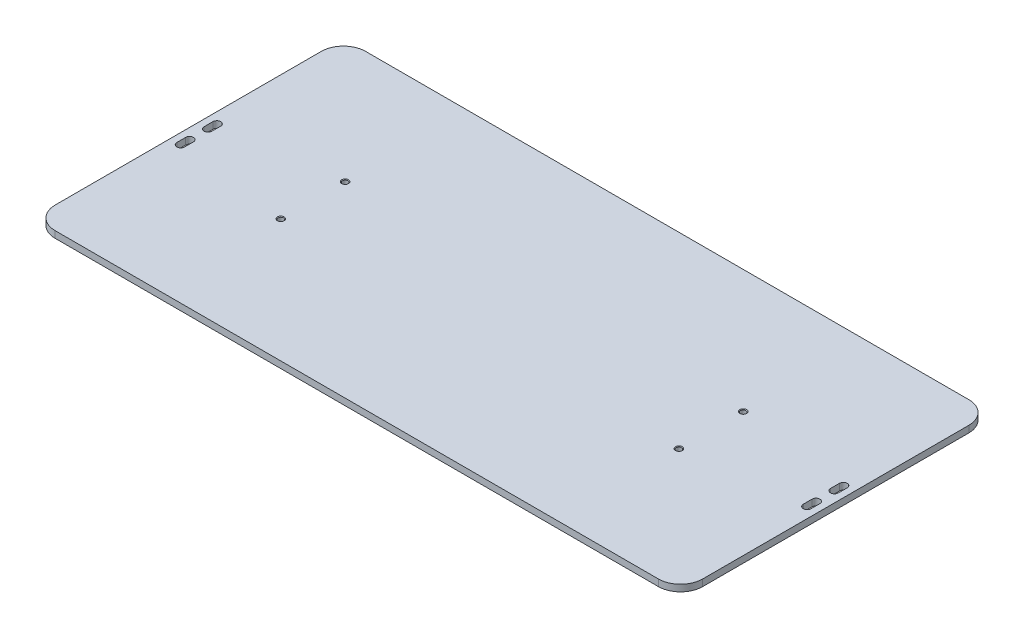
SolidWorks part; units mm, degrees
material "延性铁"
ref_plane "前视基准面" through (0, 0, 0) normal (0, 0, 1) x (1, 0, 0)
ref_plane "上视基准面" through (0, 0, 0) normal (0, 1, 0) x (1, 0, 0)
ref_plane "右视基准面" through (0, 0, 0) normal (1, 0, 0) x (0, 0, -1)
sketch "草图1" plane through (0, 0, 0) normal (0, 1, 0) x (1, 0, 0)
  line L0 (-146, 0) -> (146, 0) construction
  line L1 (-146, -70) -> (146, -70)
  line L2 (-146, -70) -> (-146, 70)
  line L3 (-146, 70) -> (146, 70)
  line L4 (146, -70) -> (146, 70)
  line L5 (-146, -70) -> (146, 70) construction
  line L6 (-146, 70) -> (146, -70) construction
  line L7 (0, 70) -> (0, -70) construction
  line L8 (-141.24, 8.14) -> (-141.24, 4.16) construction
  line L9 (-139.48, 8.14) -> (-139.48, 4.16)
  line L10 (-143, 8.14) -> (-143, 4.16)
  line L11 (-141.24, -8.14) -> (-141.24, -4.16) construction
  line L12 (-139.48, -8.14) -> (-139.48, -4.16)
  line L13 (-143, -8.14) -> (-143, -4.16)
  line L14 (141.24, 8.14) -> (141.24, 4.16) construction
  line L15 (139.48, 8.14) -> (139.48, 4.16)
  line L16 (143, 8.14) -> (143, 4.16)
  line L17 (141.24, -8.14) -> (141.24, -4.16) construction
  line L18 (139.48, -8.14) -> (139.48, -4.16)
  line L19 (143, -8.14) -> (143, -4.16)
  arc A1 (-139.48, 8.14) -> (-143, 8.14) centre (-141.24, 8.14) ccw
  arc A2 (-143, 4.16) -> (-139.48, 4.16) centre (-141.24, 4.16) ccw
  arc A3 (-139.48, -8.14) -> (-143, -8.14) centre (-141.24, -8.14) cw
  arc A4 (-143, -4.16) -> (-139.48, -4.16) centre (-141.24, -4.16) cw
  arc A5 (139.48, 8.14) -> (143, 8.14) centre (141.24, 8.14) cw
  arc A6 (143, 4.16) -> (139.48, 4.16) centre (141.24, 4.16) cw
  arc A7 (139.48, -8.14) -> (143, -8.14) centre (141.24, -8.14) ccw
  arc A8 (143, -4.16) -> (139.48, -4.16) centre (141.24, -4.16) ccw
  point P0 (0, 0)
  point P12 (-141.24, 6.15)
  point P19 (-141.24, -6.15)
  point P26 (141.24, 6.15)
  point P33 (141.24, -6.15)
  dimension "D3" = 3.52
  dimension "D4" = 3.98
  dimension "D6" = 8.32
  dimension "D1" = 140
  dimension "D2" = 292
  dimension "D5" = 3
extrude "凸台-拉伸1" add sketch "草图1" along normal blind 3
hole_wizard "M3 螺纹孔1" positions "3D草图1" profile "草图3" tap size "M3" standard "GB" end condition through all
sketch3d "3D草图1"
  line L0 (146, 3, -70) -> (-146, 3, -70) construction
  line L1 (-146, 3, -70) -> (-146, 3, 70) construction
  point P0 (-89.75, 3, -14.5)
  dimension "D1" = 55.5
  dimension "D2" = 56.25
sketch "草图3" plane through (-89.75, 3, -14.5) normal (1, 0, 0) x (0, 0, 1)
  line L0 (0, 0) -> (0, 3)
  line L1 (0, 3) -> (1.25, 3)
  line L2 (1.25, 3) -> (1.25, 0.275)
  line L3 (1.25, 0.275) -> (1.525, 0)
  line L5 (1.525, 0) -> (0, 0)
  line L6 (-1.25, 0.275) -> (-1.525, 0) construction
  line L11 (0, -6.35) -> (0, 107.95) construction
  dimension "通孔螺纹孔钻头直径" = 2.5
  dimension "通孔螺纹孔钻头深度" = 3
  dimension "近端锥形沉头孔直径" = 3.05
  dimension "近端锥形沉头孔角度" = 90
cosmetic thread "孔螺蚊线1" parameters "D2"=3
mirror "镜向1" about plane through (0, 0, 0) normal (1, 0, 0) of "M3 螺纹孔1"
cosmetic thread "孔螺蚊线2" parameters "D2"=3
mirror "镜向2" about plane through (0, 0, 0) normal (0, 0, 1) of "镜向1", "M3 螺纹孔1"
cosmetic thread "孔螺蚊线3" parameters "D2"=3
cosmetic thread "孔螺蚊线4" parameters "D2"=3
fillet "圆角1" radius 10 4 edges at (146, 1.5, 70) (-146, 1.5, 70) (146, 1.5, -70) (-146, 1.5, -70)
